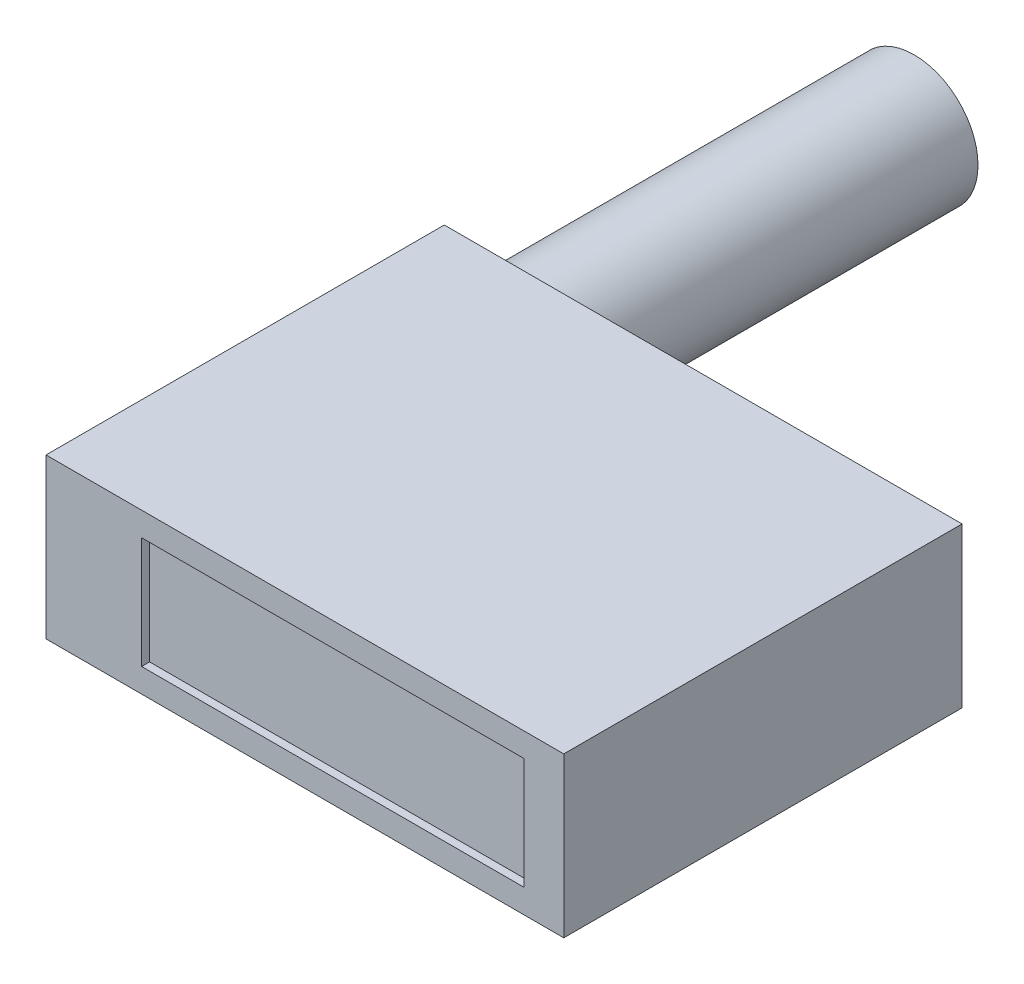
SolidWorks part; units mm, degrees
ref_plane "Front Plane" through (0, 0, 0) normal (0, 0, 1) x (1, 0, 0)
ref_plane "Top Plane" through (0, 0, 0) normal (0, 1, 0) x (1, 0, 0)
ref_plane "Right Plane" through (0, 0, 0) normal (1, 0, 0) x (0, 0, -1)
sketch "Sketch2" plane through (0, 0, 0) normal (0, 1, 0) x (1, 0, 0)
  line L1 (-32.5, 25) -> (32.5, 25)
  line L2 (-32.5, 25) -> (-32.5, -25)
  line L3 (-32.5, -25) -> (32.5, -25)
  line L4 (32.5, 25) -> (32.5, -25)
  line L5 (-32.5, 25) -> (32.5, -25) construction
  line L6 (-32.5, -25) -> (32.5, 25) construction
  point P0 (0, 0)
  dimension "D1" = 65
  dimension "D2" = 50
extrude "Boss-Extrude1" add sketch "Sketch2" along normal blind 20
sketch "Sketch4" plane through (0, 0, 25) normal (0, 0, 1) x (1, 0, 0)
  line L0 (-32.5, 10) -> (32.5, 10) construction
  line L1 (-32.5, 20) -> (-32.5, 0) construction
  line L2 (32.5, 20) -> (32.5, 0) construction
  line L4 (-20.5, 17) -> (27.5, 17)
  line L5 (-20.5, 17) -> (-20.5, 3)
  line L6 (-20.5, 3) -> (27.5, 3)
  line L7 (27.5, 17) -> (27.5, 3)
  line L8 (-20.5, 17) -> (27.5, 3) construction
  line L9 (-20.5, 3) -> (27.5, 17) construction
  point P6 (3.5, 10)
  dimension "D1" = 12
  dimension "D2" = 48
  dimension "D3" = 14
extrude "Cut-Extrude1" cut sketch "Sketch4" against normal blind 1
sketch "Sketch5" plane through (0, 0, -25) normal (0, 0, -1) x (-1, 0, 0)
  line L0 (32.5, 10) -> (-32.5, 10) construction
  line L1 (32.5, 20) -> (32.5, 0) construction
  line L2 (-32.5, 20) -> (-32.5, 0) construction
  circle A0 centre (23.5, 10) radius 8
  dimension "D1" = 16
  dimension "D2" = 9
extrude "Boss-Extrude2" add sketch "Sketch5" along normal blind 50
